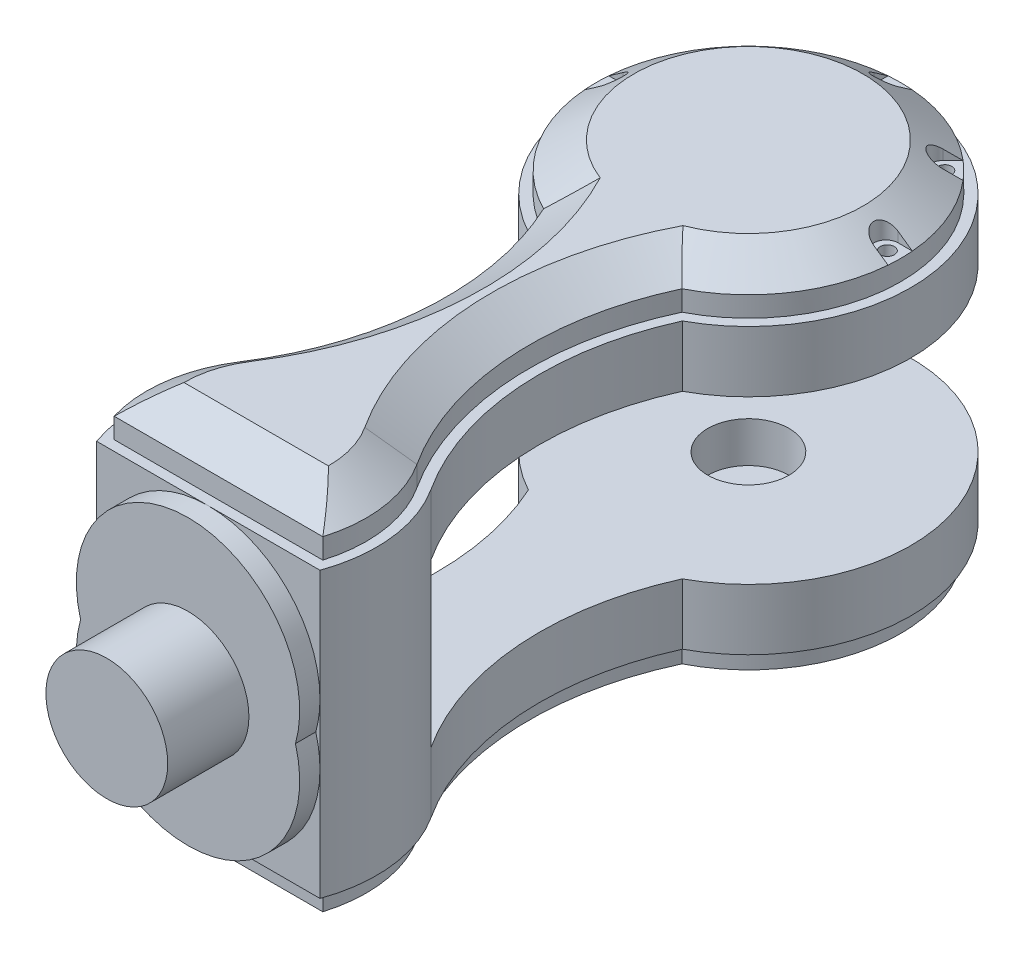
SolidWorks part; units mm, degrees
ref_plane "Front Plane" through (0, 0, 0) normal (0, 0, 1) x (1, 0, 0)
ref_plane "Top Plane" through (0, 0, 0) normal (0, 1, 0) x (1, 0, 0)
ref_plane "Right Plane" through (0, 0, 0) normal (1, 0, 0) x (0, 0, -1)
sketch "Sketch1" plane through (0, 0, 0) normal (0, 0, 1) x (1, 0, 0)
  circle A0 centre (0, 0) radius 27.5
  dimension "D1" = 55
extrude "Boss-Extrude1" add sketch "Sketch1" along normal blind 5
ref_plane "Plane1" through (27.5, 0, 0) normal (-1, 0, 0) x (0, 0, 1)
ref_plane "Plane3" through (0, 27.5, 0) normal (0, 1, 0) x (1, 0, 0)
sketch "Sketch3" plane through (0, 27.5, 0) normal (0, 1, 0) x (1, 0, 0)
  line L0 (0, 0) -> (0, 23) construction
  line L1 (-27.5, 0) -> (27.5, 0)
  arc A0 (-27.5, 0) -> (-23.9545, 30.8721) centre (5.4301, 11.8578) cw
  arc A1 (-23.9545, 30.8721) -> (-18.9577, 97.7778) centre (-82.7238, 68.9006) ccw
  arc A2 (27.5, 0) -> (23.9545, 30.8721) centre (-5.4301, 11.8578) ccw
  arc A3 (23.9545, 30.8721) -> (18.9577, 97.7778) centre (82.7238, 68.9006) cw
  arc A4 (18.9577, 97.7778) -> (-18.9577, 97.7778) centre (0, 133) ccw
  dimension "D2" = 70
  dimension "D3" = 80
  dimension "D5" = 80
  dimension "D6" = 35
  dimension "D1" = 23
  dimension "D4" = 110
extrude "Boss-Extrude2" add sketch "Sketch3" along normal blind 15 separate body
sketch "Sketch5" plane through (0, 42.5, 0) normal (0, 1, 0) x (1, 0, 0)
  line L2 (-25.6935, 2.5) -> (25.6935, 2.5)
  line L3 (-25.6935, 2.5) -> (25.6935, 2.5)
  arc A20 (-21.8556, 29.5139) -> (-25.6935, 2.5) centre (5.4301, 11.8578) ccw
  arc A21 (25.6935, 2.5) -> (21.8556, 29.5139) centre (-5.4301, 11.8578) ccw
  arc A22 (17.0426, 99.5964) -> (21.8556, 29.5139) centre (82.7238, 68.9006) ccw
  arc A23 (17.0426, 99.5964) -> (-17.0426, 99.5964) centre (0, 133) ccw
  arc A24 (-21.8556, 29.5139) -> (-17.0426, 99.5964) centre (-82.7238, 68.9006) ccw
  arc A25 (-21.8556, 29.5139) -> (-25.6935, 2.5) centre (5.4301, 11.8578) ccw
  arc A26 (25.6935, 2.5) -> (21.8556, 29.5139) centre (-5.4301, 11.8578) ccw
  arc A27 (17.0426, 99.5964) -> (21.8556, 29.5139) centre (82.7238, 68.9006) ccw
  arc A28 (17.0426, 99.5964) -> (-17.0426, 99.5964) centre (0, 133) ccw
  arc A29 (-21.8556, 29.5139) -> (-17.0426, 99.5964) centre (-82.7238, 68.9006) ccw
  dimension "D1" = 2.5
extrude "Boss-Extrude3" add sketch "Sketch5" along normal blind 1
sketch "Sketch9" plane through (0, 43.5, 0) normal (0, 1, 0) x (1, 0, 0)
  line L1 (-27.5, 0) -> (27.5, 0)
  line L2 (-27.5, 0) -> (27.5, 0)
  arc A0 (-23.9545, 30.8721) -> (-18.9577, 97.7778) centre (-82.7238, 68.9006) ccw construction
  arc A1 (-23.9545, 30.8721) -> (-18.9577, 97.7778) centre (-82.7238, 68.9006) ccw
  arc A7 (-23.9545, 30.8721) -> (-27.5, 0) centre (5.4301, 11.8578) ccw
  arc A8 (27.5, 0) -> (23.9545, 30.8721) centre (-5.4301, 11.8578) ccw
  arc A9 (18.9577, 97.7778) -> (23.9545, 30.8721) centre (82.7238, 68.9006) ccw
  arc A10 (18.9577, 97.7778) -> (-18.9577, 97.7778) centre (0, 133) ccw
  arc A11 (-23.9545, 30.8721) -> (-18.9577, 97.7778) centre (-82.7238, 68.9006) ccw
  arc A12 (-23.9545, 30.8721) -> (-27.5, 0) centre (5.4301, 11.8578) ccw
  arc A13 (27.5, 0) -> (23.9545, 30.8721) centre (-5.4301, 11.8578) ccw
  arc A14 (18.9577, 97.7778) -> (23.9545, 30.8721) centre (82.7238, 68.9006) ccw
  arc A15 (18.9577, 97.7778) -> (-18.9577, 97.7778) centre (0, 133) ccw
  arc A16 (-23.9545, 30.8721) -> (-18.9577, 97.7778) centre (-82.7238, 68.9006) ccw
  arc M1 (-17.0426, 99.5964) -> (-21.8556, 29.5139) centre (-82.7238, 68.9006) cw
  arc M2 (-21.8556, 29.5139) -> (-25.6935, 2.5) centre (5.4301, 11.8578) ccw
  line M3 (-25.6935, 2.5) -> (25.6935, 2.5)
  arc M4 (25.6935, 2.5) -> (21.8556, 29.5139) centre (-5.4301, 11.8578) ccw
  arc M5 (21.8556, 29.5139) -> (17.0426, 99.5964) centre (82.7238, 68.9006) cw
  arc M6 (17.0426, 99.5964) -> (-17.0426, 99.5964) centre (0, 133) ccw
  dimension "D1" = 0
extrude "Boss-Extrude4" add sketch "Sketch9" along normal blind 4 contours M6 M1 M2 M3 M4 M5
sketch "Sketch10" plane through (0, 47.5, 0) normal (0, 1, 0) x (1, 0, 0)
  line L1 (-25.6935, 2.5) -> (25.6935, 2.5)
  line L2 (-25.6935, 2.5) -> (25.6935, 2.5)
  arc A5 (17.0426, 99.5964) -> (-17.0426, 99.5964) centre (0, 133) ccw
  arc A6 (-21.8556, 29.5139) -> (-17.0426, 99.5964) centre (-82.7238, 68.9006) ccw
  arc A7 (-21.8556, 29.5139) -> (-25.6935, 2.5) centre (5.4301, 11.8578) ccw
  arc A8 (25.6935, 2.5) -> (21.8556, 29.5139) centre (-5.4301, 11.8578) ccw
  arc A9 (17.0426, 99.5964) -> (21.8556, 29.5139) centre (82.7238, 68.9006) ccw
  arc A10 (17.0426, 99.5964) -> (-17.0426, 99.5964) centre (0, 133) ccw
  arc A11 (-21.8556, 29.5139) -> (-17.0426, 99.5964) centre (-82.7238, 68.9006) ccw
  arc A12 (-21.8556, 29.5139) -> (-25.6935, 2.5) centre (5.4301, 11.8578) ccw
  arc A13 (25.6935, 2.5) -> (21.8556, 29.5139) centre (-5.4301, 11.8578) ccw
  arc A14 (17.0426, 99.5964) -> (21.8556, 29.5139) centre (82.7238, 68.9006) ccw
  dimension "D1" = 0
extrude "Boss-Extrude5" add sketch "Sketch10" along normal blind 6.5 draft 55
sketch "Sketch11" plane through (0, 54, 0) normal (0, 1, 0) x (1, 0, 0)
  line L0 (0, 0) -> (0, 173) construction
  line L1 (-3, 172.8873) -> (-3, 166.8873)
  line L2 (3, 172.8873) -> (3, 166.8873)
  arc A0 (18.9577, 97.7778) -> (-18.9577, 97.7778) centre (0, 133) ccw construction
  arc A1 (-3, 166.8873) -> (3, 166.8873) centre (0, 166.8873) ccw
  arc A2 (-3, 172.8873) -> (3, 172.8873) centre (0, 168.8873) cw
  dimension "D3" = 3
  dimension "D4" = 5
  dimension "D1" = 3
  dimension "D2" = 6
extrude "Cut-Extrude1" cut sketch "Sketch11" against normal blind 6.5
sketch "Sketch13" plane through (0, 47.5, 0) normal (0, 1, 0) x (1, 0, 0)
  line L0 (0, 163.8873) -> (0, 170.5) construction
  arc A0 (-3, 166.8873) -> (3, 166.8873) centre (0, 166.8873) ccw construction
  arc A1 (3, 170.3798) -> (-3, 170.3798) centre (0, 133) ccw construction
  circle A2 centre (0, 167.1937) radius 1.75
  dimension "D1" = 3.5
extrude "Cut-Extrude8" cut sketch "Sketch13" against normal blind 5 contours A2
pattern_circular "CirPattern1" count 3 every 45 about axis through (0, 0, -133) along (0, 1, 0) of "Cut-Extrude8", "Cut-Extrude1"
sketch "Sketch14" plane through (0, 27.5, 0) normal (0, -1, 0) x (1, 0, 0)
  line L0 (-23.9545, -30.8721) -> (23.9545, -30.8721)
  line L1 (27.5, 0) -> (-27.5, 0)
  line L2 (27.5, 0) -> (-27.5, 0)
  arc A5 (-27.5, 0) -> (-23.9545, -30.8721) centre (5.4301, -11.8578) ccw
  arc A6 (-18.9577, -97.7778) -> (-23.9545, -30.8721) centre (-82.7238, -68.9006) ccw
  arc A7 (-18.9577, -97.7778) -> (18.9577, -97.7778) centre (0, -133) ccw
  arc A8 (23.9545, -30.8721) -> (18.9577, -97.7778) centre (82.7238, -68.9006) ccw
  arc A9 (23.9545, -30.8721) -> (27.5, 0) centre (-5.4301, -11.8578) ccw
  arc A10 (-27.5, 0) -> (-23.9545, -30.8721) centre (5.4301, -11.8578) ccw
  arc A14 (23.9545, -30.8721) -> (27.5, 0) centre (-5.4301, -11.8578) ccw
  dimension "D1" = 0
extrude "Boss-Extrude6" add sketch "Sketch14" along normal blind 40
ref_plane "Plane4" through (0, 7.5, 0) normal (0, -1, 0) x (-1, 0, 0)
mirror "Mirror2" about plane through (0, 7.5, 0) normal (0, -1, 0) of bodies 110
sketch "Sketch15" plane through (0, 0, 5) normal (0, 0, 1) x (1, 0, 0)
  line L0 (-26.4575, 7.5) -> (26.4575, 7.5) construction
  circle A0 centre (0, 7.5) radius 15
  dimension "D1" = 30
extrude "Boss-Extrude7" add sketch "Sketch15" along normal blind 20
sketch "Sketch16" plane through (0, 27.5, 0) normal (0, -1, 0) x (1, 0, 0)
  circle A0 centre (0, -133) radius 10
  dimension "D1" = 20
extrude "Cut-Extrude9" cut sketch "Sketch16" against normal blind 10
mirror "Mirror6" about plane through (0, 7.5, 0) normal (0, -1, 0) of "Cut-Extrude9"
scale "Scale1" bodies to scale 115 scale about centroid uniform scaling yes scale factor 25.39878
